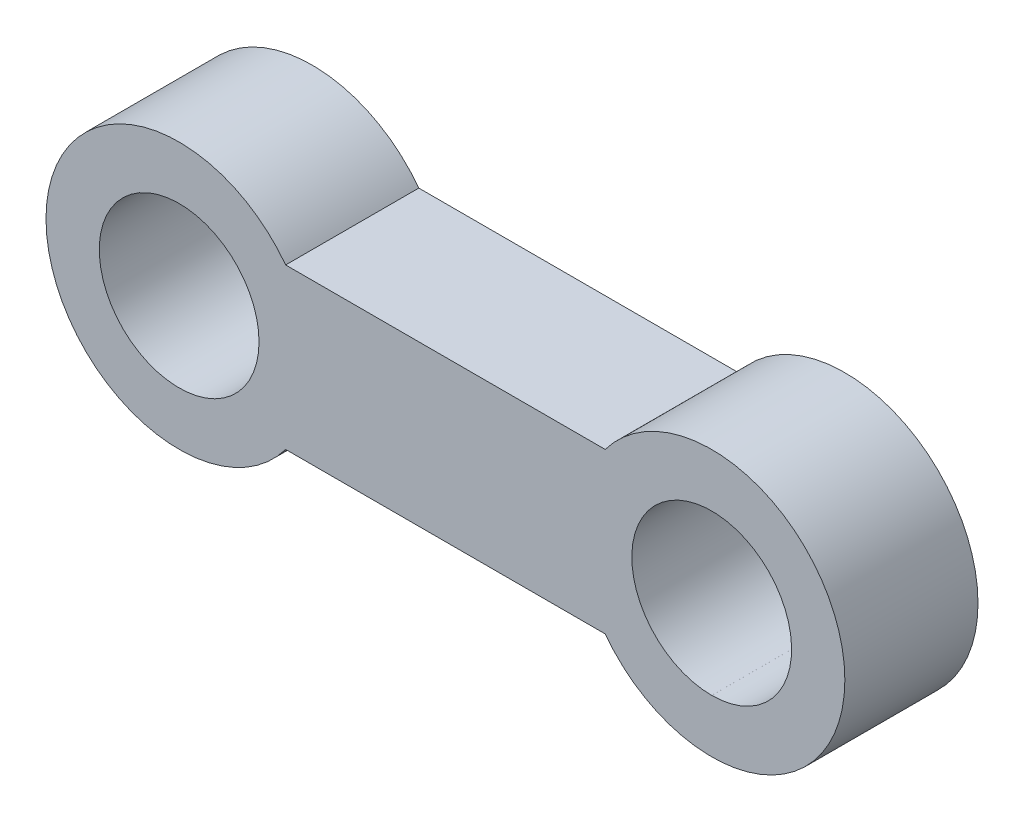
SolidWorks part; units mm, degrees
ref_plane "前视基准面" through (0, 0, 0) normal (0, 0, 1) x (1, 0, 0)
ref_plane "上视基准面" through (0, 0, 0) normal (0, 1, 0) x (1, 0, 0)
ref_plane "右视基准面" through (0, 0, 0) normal (1, 0, 0) x (0, 0, -1)
sketch "草图1" plane through (0, 0, 0) normal (0, 0, 1) x (1, 0, 0)
  line L0 (4, 3) -> (16, 3)
  line L1 (4, -3) -> (16, -3)
  line L2 (20, -3) -> (20.0018, -3)
  circle A0 centre (0, 0) radius 3
  arc A1 (4, 3) -> (4, -3) centre (0, 0) ccw
  arc A2 (16, -3) -> (16, 3) centre (20, 0) ccw
  circle A3 centre (20, 0) radius 3
extrude "凸台-拉伸1" add sketch "草图1" along normal blind 5 contours L1 A2 L0 A1 A3 L2 A0
